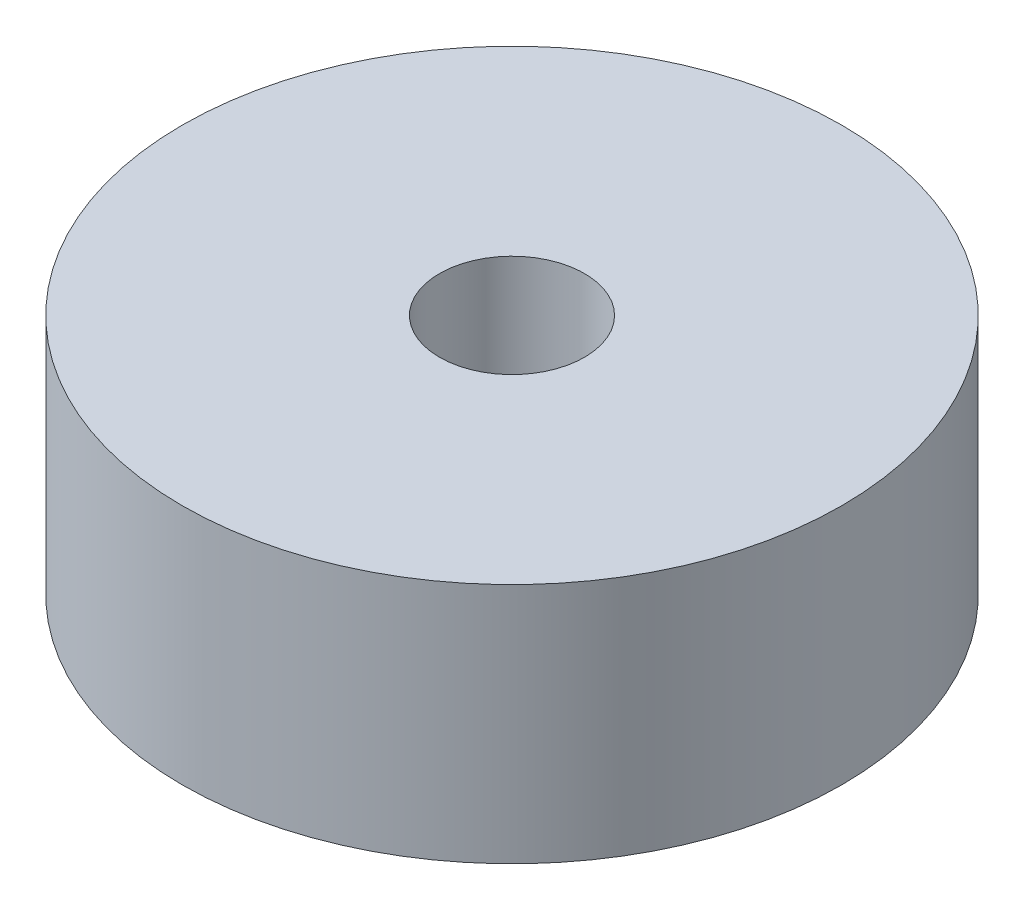
SolidWorks part; units mm, degrees
ref_plane "Ebene vorne" through (0, 0, 0) normal (0, 0, 1) x (1, 0, 0)
ref_plane "Ebene oben" through (0, 0, 0) normal (0, 1, 0) x (1, 0, 0)
ref_plane "Ebene rechts" through (0, 0, 0) normal (1, 0, 0) x (0, 0, -1)
sketch "Skizze1" plane through (0, 0, 0) normal (0, 1, 0) x (1, 0, 0)
  circle A0 centre (0, 0) radius 15
  circle A1 centre (0, 0) radius 3.3
  dimension "D1" = 30
  dimension "D2" = 6.6
extrude "Aufsatz-Linear austragen1" add sketch "Skizze1" along normal blind 11
